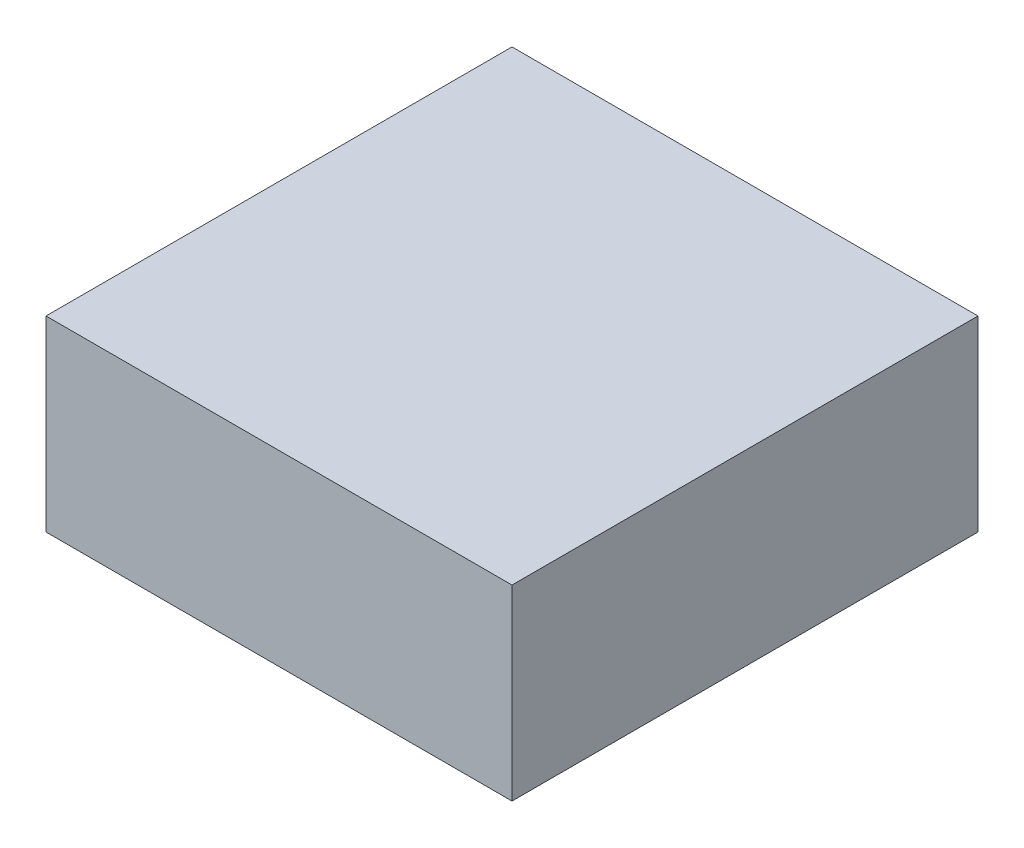
SolidWorks part; units mm, degrees
ref_plane "Front Plane" through (0, 0, 0) normal (0, 0, 1) x (1, 0, 0)
ref_plane "Top Plane" through (0, 0, 0) normal (0, 1, 0) x (1, 0, 0)
ref_plane "Right Plane" through (0, 0, 0) normal (1, 0, 0) x (0, 0, -1)
sketch "Sketch2" plane through (0, 0, 0) normal (0, 1, 0) x (1, 0, 0)
  line L1 (-3.91, 3.91) -> (3.91, 3.91)
  line L2 (-3.91, 3.91) -> (-3.91, -3.91)
  line L3 (-3.91, -3.91) -> (3.91, -3.91)
  line L4 (3.91, 3.91) -> (3.91, -3.91)
  line L5 (-3.91, 3.91) -> (3.91, -3.91) construction
  line L6 (-3.91, -3.91) -> (3.91, 3.91) construction
  point P0 (0, 0)
  dimension "D1" = 7.82
  dimension "D2" = 7.82
extrude "Boss-Extrude1" add sketch "Sketch2" against normal blind 3.14
shell "Shell1" thickness 1.5
